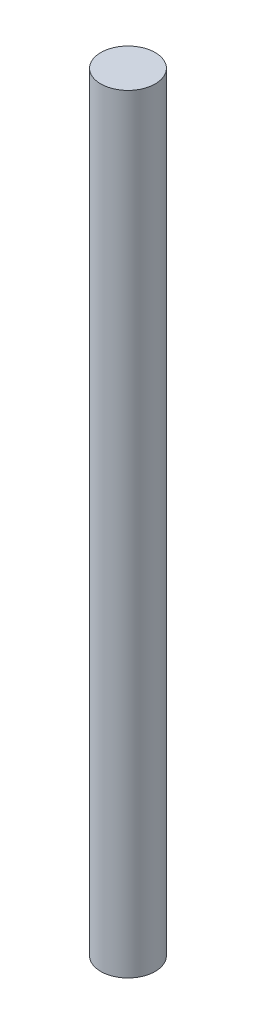
SolidWorks part; units mm, degrees
ref_plane "Front Plane" through (0, 0, 0) normal (0, 0, 1) x (1, 0, 0)
ref_plane "Top Plane" through (0, 0, 0) normal (0, 1, 0) x (1, 0, 0)
ref_plane "Right Plane" through (0, 0, 0) normal (1, 0, 0) x (0, 0, -1)
sketch "Sketch1" plane through (0, 0, 0) normal (0, 1, 0) x (1, 0, 0)
  circle A0 centre (0, 0) radius 4
  dimension "D1" = 8
extrude "Boss-Extrude1" add sketch "Sketch1" along normal blind 113
sketch "Sketch2" plane through (0, 113, 0) normal (0, 1, 0) x (1, 0, 0)
  circle A0 centre (0, 0) radius 3
  dimension "D1" = 6
